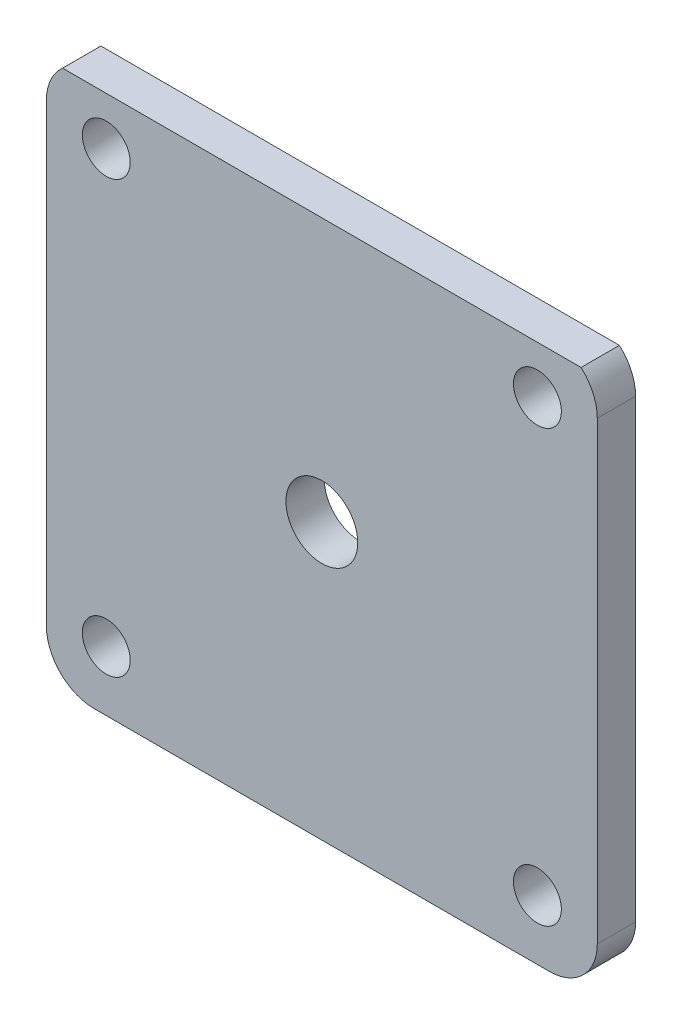
SolidWorks part; units mm, degrees
ref_plane "Front Plane" through (0, 0, 0) normal (0, 0, 1) x (1, 0, 0)
ref_plane "Top Plane" through (0, 0, 0) normal (0, 1, 0) x (1, 0, 0)
ref_plane "Right Plane" through (0, 0, 0) normal (1, 0, 0) x (0, 0, -1)
sketch "Sketch1" plane through (0, 0, 0) normal (0, 0, 1) x (1, 0, 0)
  line L0 (0, 11.5) -> (0, -11.5) construction
  line L1 (-9.5, -11.5) -> (9.5, -11.5)
  line L2 (-11.5, -9.5) -> (-11.5, 9.5)
  line L3 (-9.5, 11.5) -> (9.5, 11.5)
  line L4 (11.5, -9.5) -> (11.5, 9.5)
  line L5 (-11.5, -11.5) -> (11.5, 11.5) construction
  line L6 (-11.5, 11.5) -> (11.5, -11.5) construction
  line L7 (11.5, 0) -> (-11.5, 0) construction
  arc A0 (9.5, -11.5) -> (11.5, -9.5) centre (9.5, -9.5) ccw
  arc A1 (-9.5, -11.5) -> (-11.5, -9.5) centre (-9.5, -9.5) cw
  arc A2 (-11.5, 9.5) -> (-9.5, 11.5) centre (-9.5, 9.5) cw
  arc A3 (9.5, 11.5) -> (11.5, 9.5) centre (9.5, 9.5) cw
  circle A4 centre (0, 0) radius 1.5
  circle A5 centre (9, 9) radius 1
  circle A6 centre (-9, 9) radius 1
  circle A7 centre (-9, -9) radius 1
  circle A8 centre (9, -9) radius 1
  point P0 (0, 0)
  dimension "D3" = 2
  dimension "D4" = 3
  dimension "D5" = 2
  dimension "D6" = 2.5
  dimension "D1" = 23
  dimension "D2" = 23
  dimension "D7" = 2.5
extrude "Boss-Extrude1" add sketch "Sketch1" along normal blind 1.6
sketch "Sketch3" plane through (0, 0, 0) normal (0, 0, -1) x (-1, 0, 0)
  line L0 (-18.25, 11) -> (-18.25, 12.2497)
  line L1 (-18.25, 12.2497) -> (12.5349, 12.2497)
  line L2 (12.5349, 12.2497) -> (12.5349, 11)
  line L3 (12.5349, 11) -> (-18.25, 11)
extrude "Cut-Extrude2" cut sketch "Sketch3" against normal blind 10
